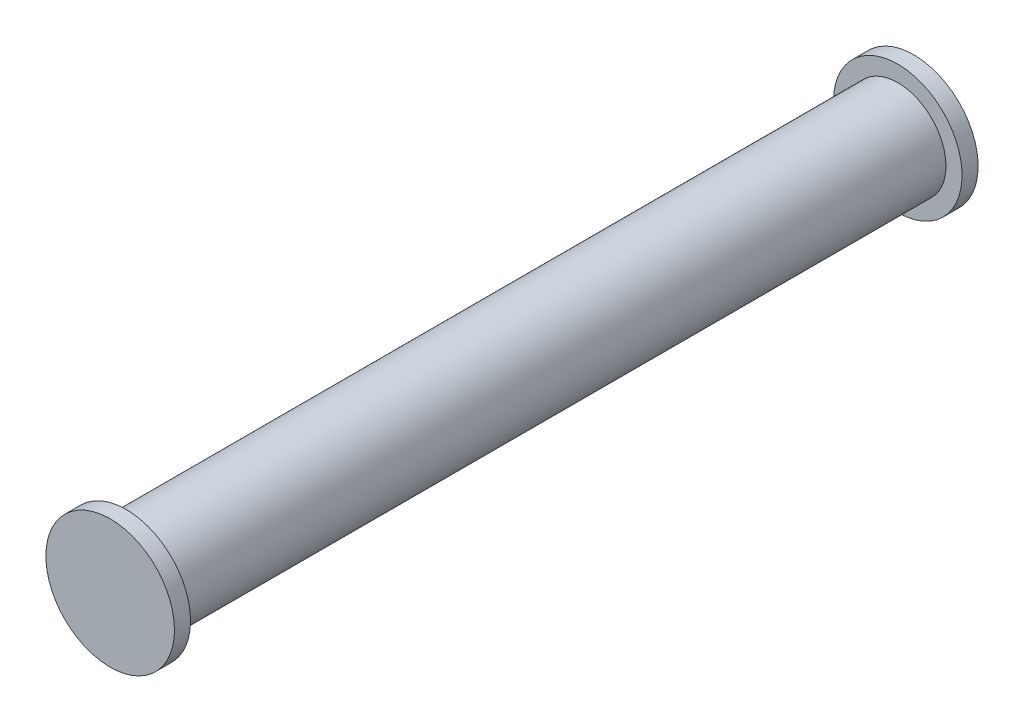
SolidWorks part; units mm, degrees
ref_plane "Front Plane" through (0, 0, 0) normal (0, 0, 1) x (1, 0, 0)
ref_plane "Top Plane" through (0, 0, 0) normal (0, 1, 0) x (1, 0, 0)
ref_plane "Right Plane" through (0, 0, 0) normal (1, 0, 0) x (0, 0, -1)
sketch "Sketch1" plane through (0, 0, 0) normal (0, 0, 1) x (1, 0, 0)
  circle A0 centre (0, 0) radius 19.05
  dimension "D1" = 38.1
extrude "Boss-Extrude1" add sketch "Sketch1" along normal blind 304.8
sketch "Sketch2" plane through (0, 0, 304.8) normal (0, 0, 1) x (1, 0, 0)
  circle A0 centre (0, 0) radius 25.4
  dimension "D1" = 50.8
extrude "Boss-Extrude2" add sketch "Sketch2" along normal blind 6.35
sketch "Sketch3" plane through (0, 0, 0) normal (0, 0, -1) x (-1, 0, 0)
  circle A0 centre (0, 0) radius 25.4
  dimension "D1" = 50.8
extrude "Boss-Extrude3" add sketch "Sketch3" along normal blind 6.35
